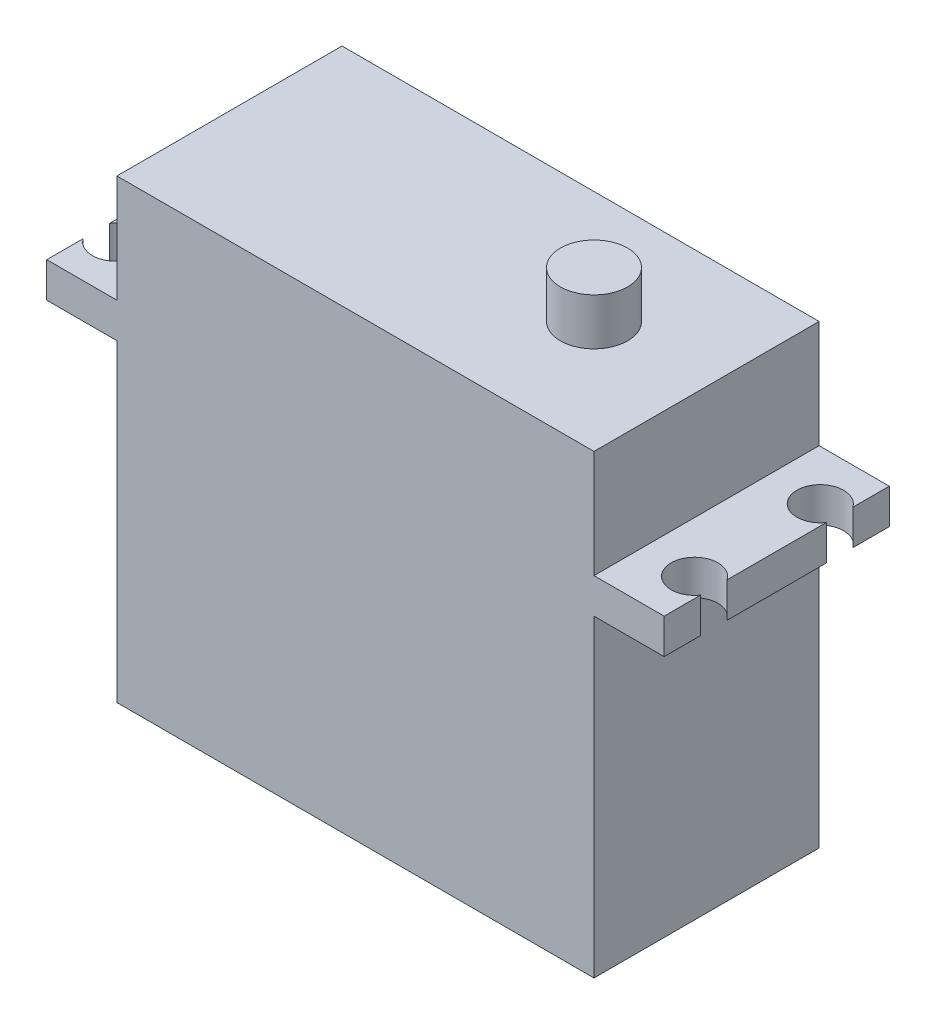
SolidWorks part; units mm, degrees
ref_plane "Front Plane" through (0, 0, 0) normal (0, 0, 1) x (1, 0, 0)
ref_plane "Top Plane" through (0, 0, 0) normal (0, 1, 0) x (1, 0, 0)
ref_plane "Right Plane" through (0, 0, 0) normal (1, 0, 0) x (0, 0, -1)
sketch "Sketch1" plane through (0, 0, 0) normal (0, 0, 1) x (1, 0, 0)
  line L0 (0, 0) -> (40.8, 0)
  line L1 (40.8, 0) -> (40.8, 26.8)
  line L2 (40.8, 26.8) -> (46.8, 26.8)
  line L3 (46.8, 26.8) -> (46.8, 29.8)
  line L4 (46.8, 29.8) -> (40.8, 29.8)
  line L5 (40.8, 29.8) -> (40.8, 39)
  line L6 (40.8, 39) -> (0, 39)
  line L7 (0, 39) -> (0, 29.8)
  line L8 (0, 29.8) -> (-6, 29.8)
  line L9 (-6, 29.8) -> (-6, 26.8)
  line L10 (-6, 26.8) -> (0, 26.8)
  line L11 (0, 26.8) -> (0, 0)
  dimension "D1" = 40.8
  dimension "D2" = 26.8
  dimension "D3" = 3
  dimension "D4" = 6
  dimension "D5" = 39
extrude "Boss-Extrude1" add sketch "Sketch1" along normal blind 19.25
sketch "Sketch2" plane through (0, 39, 0) normal (0, 1, 0) x (1, 0, 0)
  line L3 (40.8, -19.25) -> (40.8, 0) construction
  circle A1 centre (31.175, -9.625) radius 2.875
  point P2 (40.8, -9.625)
  point P3 (34.05, -9.625)
  point P6 (33.415, -10.05)
  dimension "D1" = 5.75
  dimension "D2" = 6.75
extrude "Boss-Extrude2" add sketch "Sketch2" along normal blind 4
sketch "Sketch3" plane through (0, 29.8, 0) normal (0, 1, 0) x (1, 0, 0)
  line L0 (45.15, -15) -> (45.15, -4.25) construction
  line L1 (46.8, -19.25) -> (46.8, 0) construction
  line L2 (20.4, -19.25) -> (20.4, 0) construction
  line L3 (40.8, -19.25) -> (0, -19.25) construction
  line L4 (40.8, 0) -> (0, 0) construction
  line L5 (-4.35, -15) -> (-4.35, -4.25) construction
  line L6 (46.8, 0) -> (40.8, 0) construction
  circle A0 centre (45.15, -15) radius 2
  circle A1 centre (45.15, -4.25) radius 2
  circle A2 centre (-4.35, -4.25) radius 2
  circle A3 centre (-4.35, -15) radius 2
  point P4 (45.15, -9.625)
  point P5 (46.8, -9.625)
  point P18 (-4.35, -9.625)
  point P19 (45.15, -2.25)
  point P22 (43.15, -15)
  point P23 (-2.35, -15)
  dimension "D3" = 4
  dimension "D1" = 2.25
  dimension "D2" = 45.5
extrude "Cut-Extrude1" cut sketch "Sketch3" against normal up to next
